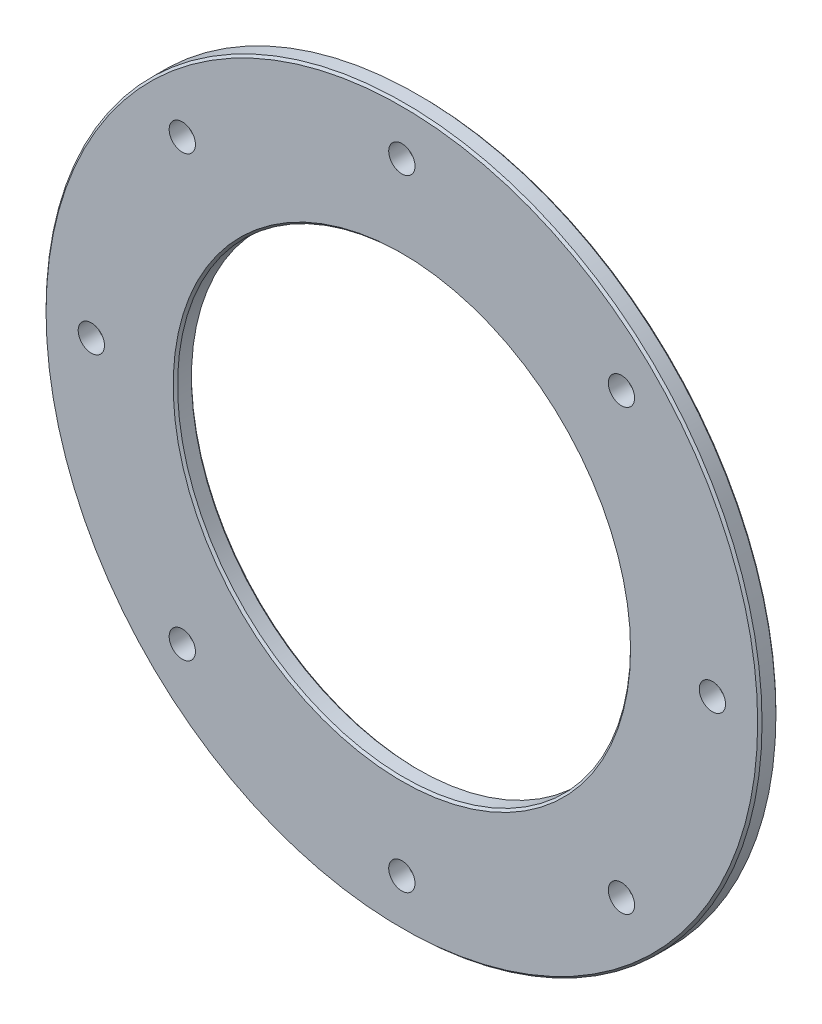
SolidWorks part; units mm, degrees
ref_plane "Front Plane" through (0, 0, 0) normal (0, 0, 1) x (1, 0, 0)
ref_plane "Top Plane" through (0, 0, 0) normal (0, 1, 0) x (1, 0, 0)
ref_plane "Right Plane" through (0, 0, 0) normal (1, 0, 0) x (0, 0, -1)
sketch "Sketch1" plane through (0, 0, 0) normal (0, 0, 1) x (1, 0, 0)
  circle A0 centre (0, 0) radius 49
  dimension "D1" = 98
extrude "Boss-Extrude1" add sketch "Sketch1" along normal blind 2.5
sketch "Sketch2" plane through (0, 0, 2.5) normal (0, 0, 1) x (1, 0, 0)
  circle A0 centre (0, 0) radius 42.5
  point P4 (0, 42.5)
  point P9 (30.052, 30.052)
  point P10 (42.5, 0)
  point P11 (30.052, -30.052)
  point P12 (0, -42.5)
  point P13 (-30.052, -30.052)
  point P14 (-42.5, 0)
  point P15 (-30.052, 30.052)
  dimension "D1" = 85
  dimension "D2" = 8
hole_wizard "M3 Clearance Hole1" positions "Sketch2" profile "Sketch3" hole size "M3" standard "DIN"
sketch "Sketch3" plane through (-30.052, 30.052, 2.5) normal (1, 0, 0) x (0, -1, 0)
  line L0 (0, 0) -> (0, 21.0815)
  line L1 (0, 21.0815) -> (1.8, 20)
  line L2 (1.8, 20) -> (1.8, 0)
  line L5 (1.8, 0) -> (0, 0)
  line L10 (0, 21.0815) -> (-1.8, 20) construction
  line L11 (0, -6.35) -> (0, 107.95) construction
  dimension "Hole Dia." = 3.6
  dimension "Hole Depth" = 20
  dimension "Drill Angle" = 118
sketch "Sketch4" plane through (0, 0, 2.5) normal (0, 0, 1) x (1, 0, 0)
  circle A0 centre (0, 0) radius 31
  dimension "D1" = 62
extrude "Cut-Extrude1" cut sketch "Sketch4" against normal through all
chamfer "Chamfer1" distance 0.3 angle 45 4 edges at (31, 0, 0) (49, 0, 0) (31, 0, 2.5) (49, 0, 2.5)
